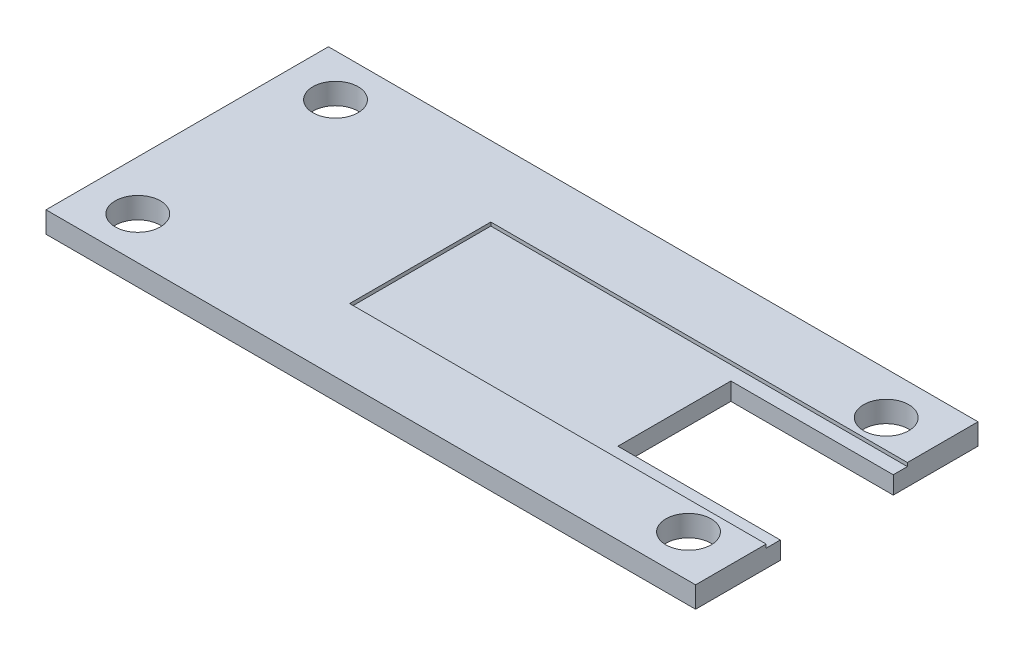
SolidWorks part; units mm, degrees
ref_plane "前视基准面" through (0, 0, 0) normal (0, 0, 1) x (1, 0, 0)
ref_plane "上视基准面" through (0, 0, 0) normal (0, 1, 0) x (1, 0, 0)
ref_plane "右视基准面" through (0, 0, 0) normal (1, 0, 0) x (0, 0, -1)
ref_plane "基准面4" through (0, 0, 0) normal (0, -1, 0) x (1, 0, 0)
sketch "草图1" plane through (0, 0, 0) normal (0, 1, 0) x (1, 0, 0)
  line L0 (0, 0) -> (0, 4.0002) construction
  line L1 (0, 0) -> (6.2226, 0) construction
  line L3 (-23, 10) -> (23, 10)
  line L4 (-23, 10) -> (-23, -10)
  line L5 (-23, -10) -> (23, -10)
  line L6 (23, 10) -> (23, -10)
  circle A0 centre (-19.5, 7) radius 1.6
  circle A1 centre (19.5, 7) radius 1.6
  circle A2 centre (19.5, -7) radius 1.6
  circle A3 centre (-19.5, -7) radius 1.6
  dimension "D1" = 3.2
  dimension "D2" = 7
  dimension "D3" = 19.5
  dimension "D4" = 46
  dimension "D5" = 20
extrude "凸台-拉伸1" add sketch "草图1" along normal blind 1.5
sketch "草图2" plane through (0, 1.5, 0) normal (0, 1, 0) x (1, 0, 0)
  line L0 (23, -10) -> (23, 10) construction
  line L1 (-6.5, 5) -> (23, 5)
  line L2 (-6.5, 5) -> (-6.5, -5)
  line L3 (-6.5, -5) -> (23, -5)
  line L4 (23, 5) -> (23, -5)
  line L5 (23, 10) -> (-23, 10) construction
  line L6 (-23, -10) -> (23, -10) construction
  dimension "D1" = 10
  dimension "D2" = 29.5
  dimension "D3" = 5
  dimension "D4" = 5
extrude "切除-拉伸1" cut sketch "草图2" against normal blind 0.25
sketch "草图3" plane through (0, 1.25, 0) normal (0, 1, 0) x (1, 0, 0)
  line L1 (11.5, 4) -> (23, 4)
  line L2 (11.5, 4) -> (11.5, -4)
  line L3 (11.5, -4) -> (23, -4)
  line L4 (23, 4) -> (23, -4)
  line L6 (-6.5, -5) -> (23, -5) construction
  line L7 (23, 5) -> (-6.5, 5) construction
  dimension "D1" = 11.5
  dimension "D2" = 8
  dimension "D3" = 1
  dimension "D4" = 1
extrude "切除-拉伸2" cut sketch "草图3" against normal blind 30.25
